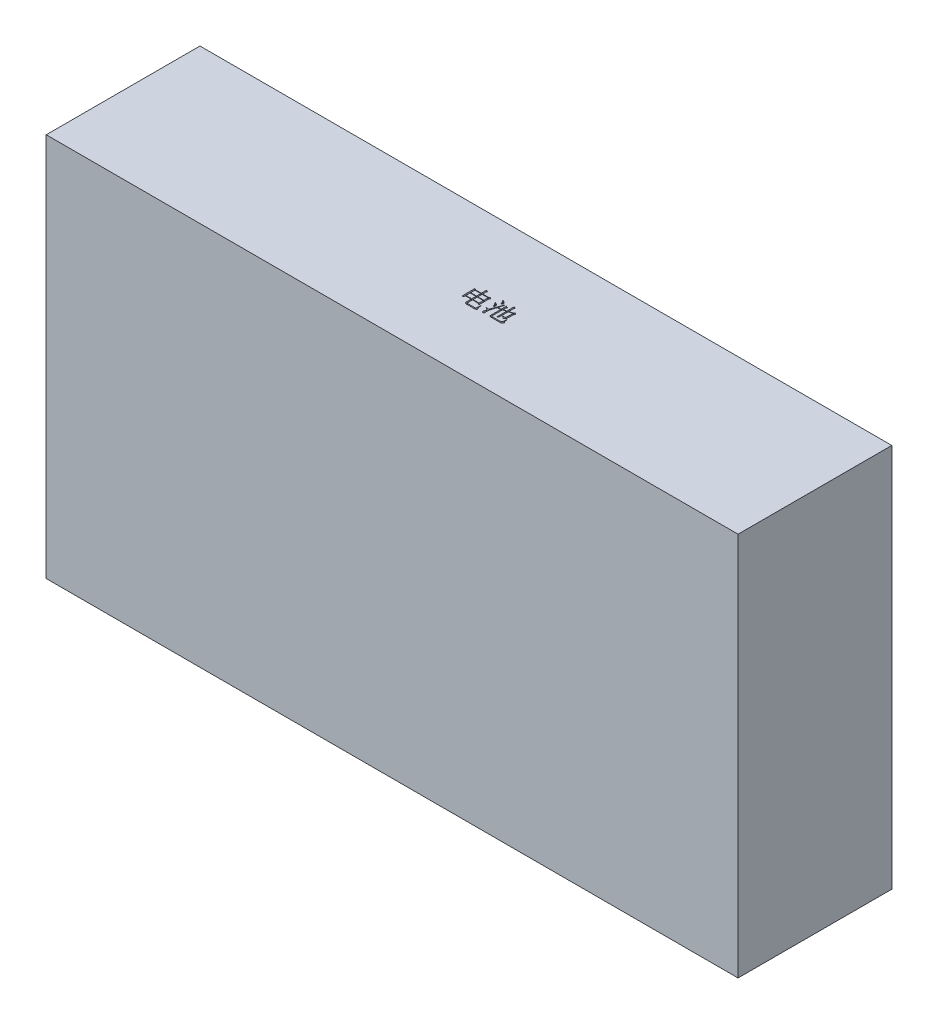
SolidWorks part; units mm, degrees
ref_plane "前视基准面" through (0, 0, 0) normal (0, 0, 1) x (1, 0, 0)
ref_plane "上视基准面" through (0, 0, 0) normal (0, 1, 0) x (1, 0, 0)
ref_plane "右视基准面" through (0, 0, 0) normal (1, 0, 0) x (0, 0, -1)
sketch "草图1" plane through (0, 0, 0) normal (0, 0, 1) x (1, 0, 0)
  line L0 (-60.5233, 0) -> (73.0814, 0) construction
  line L1 (0, 70.9884) -> (0, -62.2674) construction
  line L3 (-67.5, 37.5) -> (67.5, 37.5)
  line L4 (-67.5, 37.5) -> (-67.5, -37.5)
  line L5 (-67.5, -37.5) -> (67.5, -37.5)
  line L6 (67.5, 37.5) -> (67.5, -37.5)
  dimension "D1" = 75
  dimension "D2" = 135
  dimension "D3" = 37.5
  dimension "D4" = 67.5
extrude "凸台-拉伸1" add sketch "草图1" along normal blind 30
sketch "草图2" plane through (0, 0, 0) normal (0, 0, -1) x (-1, 0, 0)
  text T0 "电池"
extrude "切除-拉伸1" cut sketch "草图2" against normal blind 2
sketch "草图3" plane through (0, 37.5, 0) normal (0, 1, 0) x (1, 0, 0)
  text T0 "电池"
extrude "切除-拉伸2" cut sketch "草图3" against normal blind 2
